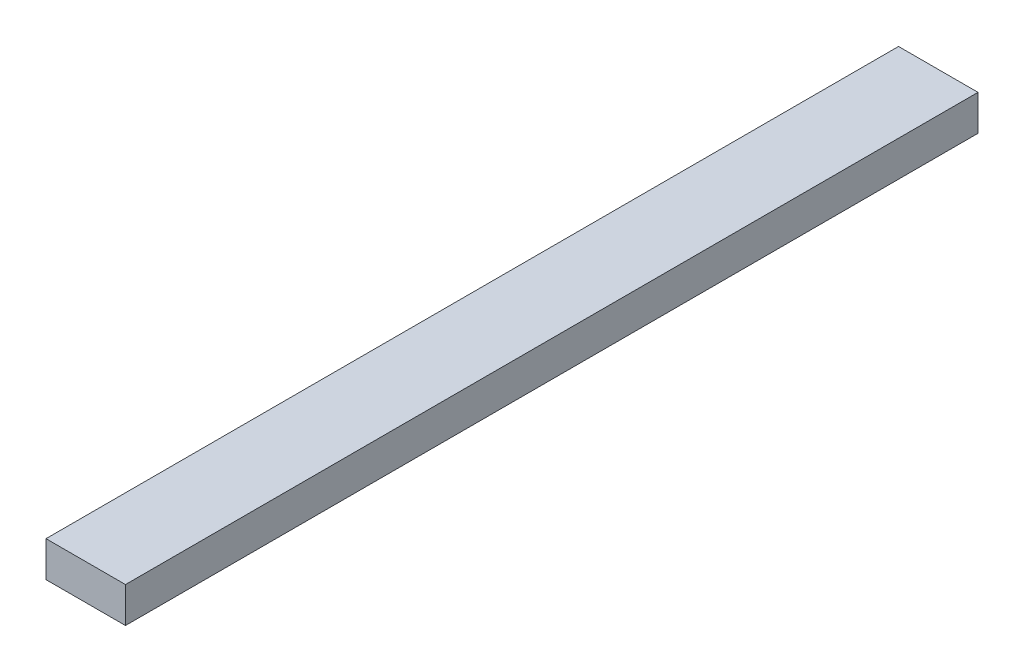
SolidWorks part; units mm, degrees
ref_plane "Front Plane" through (0, 0, 0) normal (1, 0, 0) x (0, 1, 0)
ref_plane "Top Plane" through (0, 0, 0) normal (0, 0, 1) x (0, 1, 0)
ref_plane "Right Plane" through (0, 0, 0) normal (0, 1, 0) x (-1, 0, 0)
sketch "Sketch1" plane through (0, 0, 0) normal (0, 0, 1) x (0, 1, 0)
  line L1 (-8.3312, -18.6436) -> (8.3312, -18.6436)
  line L2 (-8.3312, -18.6436) -> (-8.3312, 18.6436)
  line L3 (-8.3312, 18.6436) -> (8.3312, 18.6436)
  line L4 (8.3312, -18.6436) -> (8.3312, 18.6436)
  line L5 (-8.3312, -18.6436) -> (8.3312, 18.6436) construction
  line L6 (-8.3312, 18.6436) -> (8.3312, -18.6436) construction
  point P0 (0, 0)
  dimension "D1" = 16.6624
  dimension "D2" = 37.2872
extrude "Boss-Extrude1" add sketch "Sketch1" along normal mid plane 400
